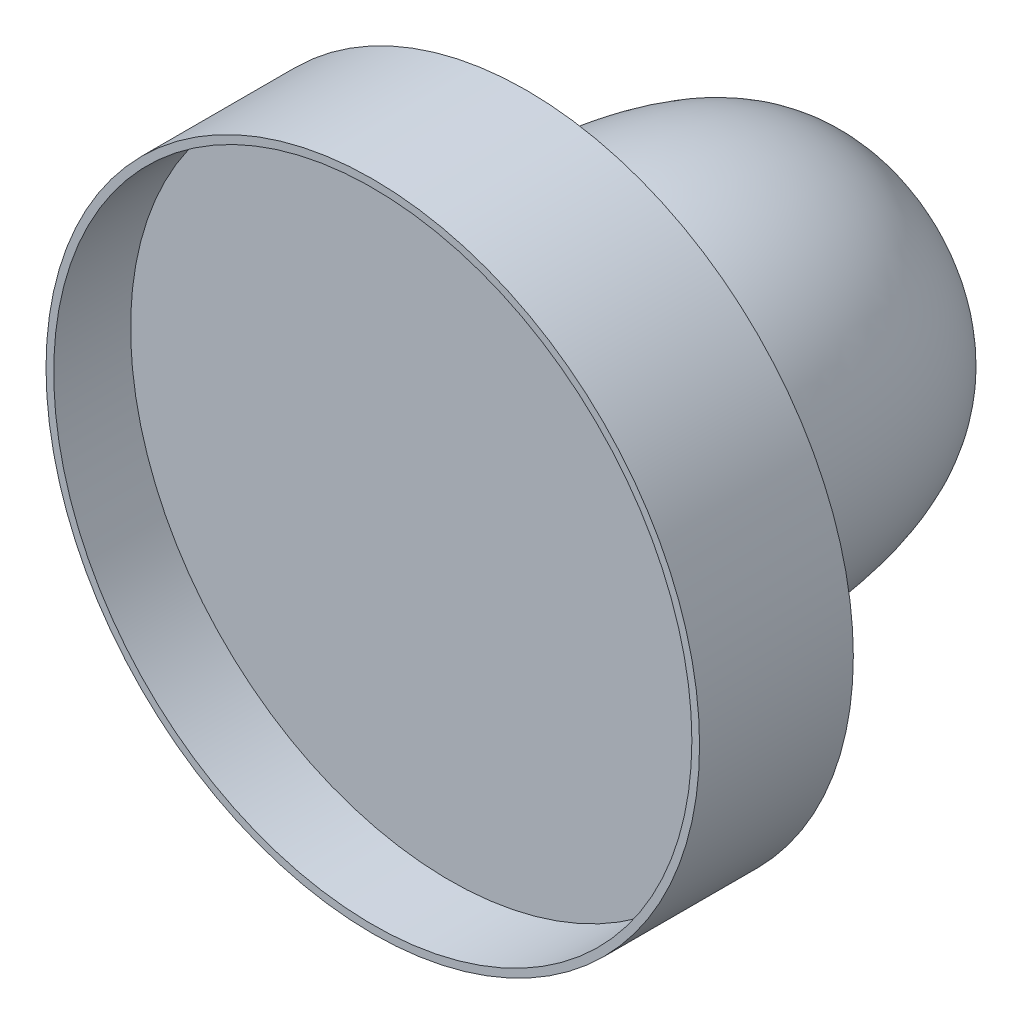
SolidWorks part; units mm, degrees
material "PE Low/Medium Density"
ref_plane "Front Plane" through (0, 0, 0) normal (0, 0, 1) x (1, 0, 0)
ref_plane "Top Plane" through (0, 0, 0) normal (0, 1, 0) x (1, 0, 0)
ref_plane "Right Plane" through (0, 0, 0) normal (1, 0, 0) x (0, 0, -1)
sketch "Sketch1" plane through (0, 0, 0) normal (0, 1, 0) x (1, 0, 0)
  line L0 (0, 6.5) -> (0, 2)
  line L1 (0, 0) -> (4.25, 0)
  line L2 (0, 0) -> (0, 2)
  line L3 (2.5699, 2) -> (4.25, 2)
  line L4 (4.25, 0) -> (4.25, 2)
  spline S0 degree 3 poles (0, 6.5) (2.6809, 6.9413) (2.5753, 4.0267) (2.5699, 2) knots 0 0 0 0 0.962492 0.962492 0.962492 0.962492
  dimension "D1" = 4.25
  dimension "D2" = 4.5
  dimension "D3" = 2
revolve "Revolve2" add sketch "Sketch1" angle 360 about L0
sketch "Sketch2" plane through (0, 0, 0) normal (0, 0, 1) x (1, 0, 0)
  circle A0 centre (0, 0) radius 4.15
  dimension "D1" = 8.3
extrude "Cut-Extrude1" cut sketch "Sketch2" against normal blind 1 contours A0
